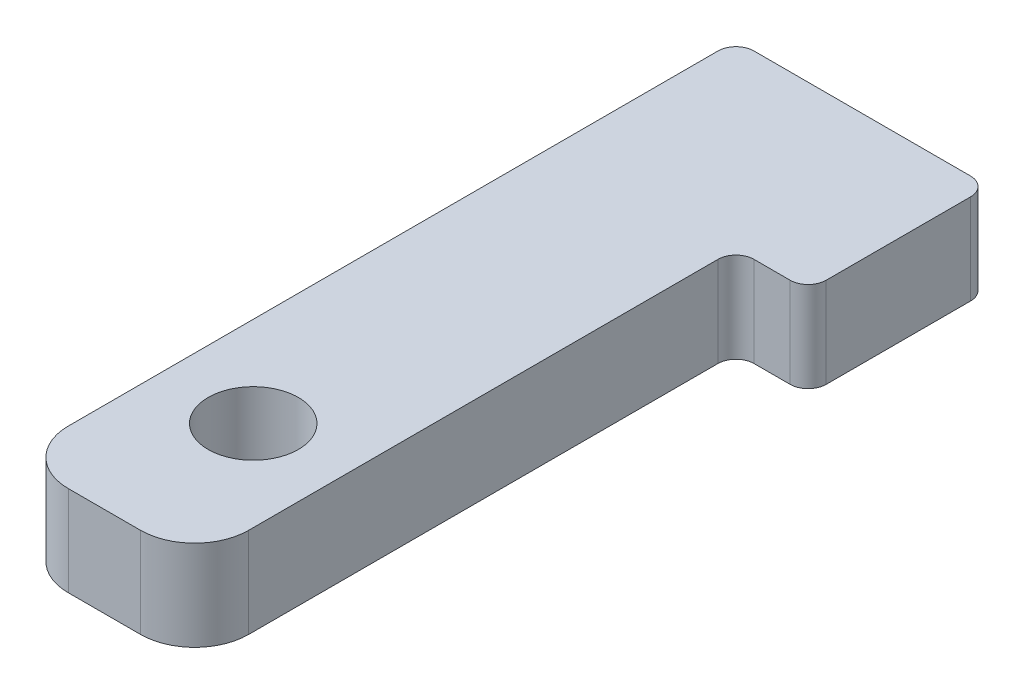
SolidWorks part; units mm, degrees
material "Медь"
ref_plane "Спереди" through (0, 0, 0) normal (0, 0, 1) x (1, 0, 0)
ref_plane "Сверху" through (0, 0, 0) normal (0, 1, 0) x (1, 0, 0)
ref_plane "Справа" through (0, 0, 0) normal (1, 0, 0) x (0, 0, -1)
sketch "Эскиз1" plane through (0, 0, 0) normal (0, 1, 0) x (1, 0, 0)
  line L0 (0, 16.5) -> (10, 16.5) construction
  line L1 (3, 0) -> (7, 0)
  line L2 (0, 3) -> (0, 30)
  line L3 (0, 30) -> (10, 30)
  line L4 (10, 3) -> (10, 30)
  line L5 (5, 16.5) -> (5, 0) construction
  circle A0 centre (5, 8.25) radius 2.5
  arc A1 (7, 0) -> (10, 3) centre (7, 3) ccw
  arc A2 (0, 3) -> (3, 0) centre (3, 3) ccw
  point P16 (0, 0)
  dimension "D2" = 10
  dimension "D3" = 5
  dimension "D4" = 3
  dimension "D1" = 30
extrude "Бобышка-Вытянуть1" add sketch "Эскиз1" along normal blind 5
sketch "Эскиз2" plane through (0, 0, -30) normal (0, 0, -1) x (-1, 0, 0)
  line L0 (-10, 5) -> (0, 5) construction
  line L1 (0, 0) -> (-10, 0)
  line L2 (0, 0) -> (0, 5)
  line L3 (0, 5) -> (-10, 5)
  line L4 (-10, 0) -> (-10, 5)
extrude "Бобышка-Вытянуть2" add sketch "Эскиз2" along normal blind 10
sketch "Эскиз3" plane through (0, 5, 0) normal (0, 1, 0) x (1, 0, 0)
  line L0 (5, 40) -> (5, 34) construction
  line L1 (0, 40) -> (10, 40) construction
  line L2 (5, 34) -> (5, 24) construction
  circle A0 centre (5, 34) radius 1.5
  circle A1 centre (5, 24) radius 1.5
  dimension "D2" = 10
  dimension "D1" = 6
sketch "Эскиз4" plane through (0, 5, 0) normal (0, 1, 0) x (1, 0, 0)
  line L0 (10, 3) -> (10, 40) construction
  line L1 (13, 40) -> (10, 40)
  line L2 (0, 40) -> (10, 40) construction
  line L4 (10, 40) -> (10, 29)
  line L5 (11, 30) -> (13, 30)
  line L6 (14, 31) -> (14, 39)
  arc A0 (11, 30) -> (10, 29) centre (11, 29) ccw
  arc A1 (13, 30) -> (14, 31) centre (13, 31) ccw
  arc A2 (14, 39) -> (13, 40) centre (13, 39) ccw
extrude "Бобышка-Вытянуть3" add sketch "Эскиз4" against normal blind 5
sketch "Эскиз5" plane through (0, 5, 0) normal (0, 1, 0) x (1, 0, 0)
  line L0 (0, 38.8926) -> (0, 39)
  line L1 (0, 40) -> (0, 3) construction
  line L2 (0, 40) -> (13, 40) construction
  line L3 (1, 40) -> (1.042, 40)
  line L4 (1.042, 40) -> (0.9489, 40.2945)
  line L5 (0.9489, 40.2945) -> (-0.4971, 40.2455)
  line L6 (-0.4971, 40.2455) -> (-0.4971, 39.4122)
  line L7 (-0.4971, 39.4122) -> (0, 38.8926)
  arc A0 (0, 39) -> (1, 40) centre (1, 39) cw
  point P12 (0, 40)
  dimension "D1" = 1
extrude "Вырез-Вытянуть1" cut sketch "Эскиз5" against normal through all
